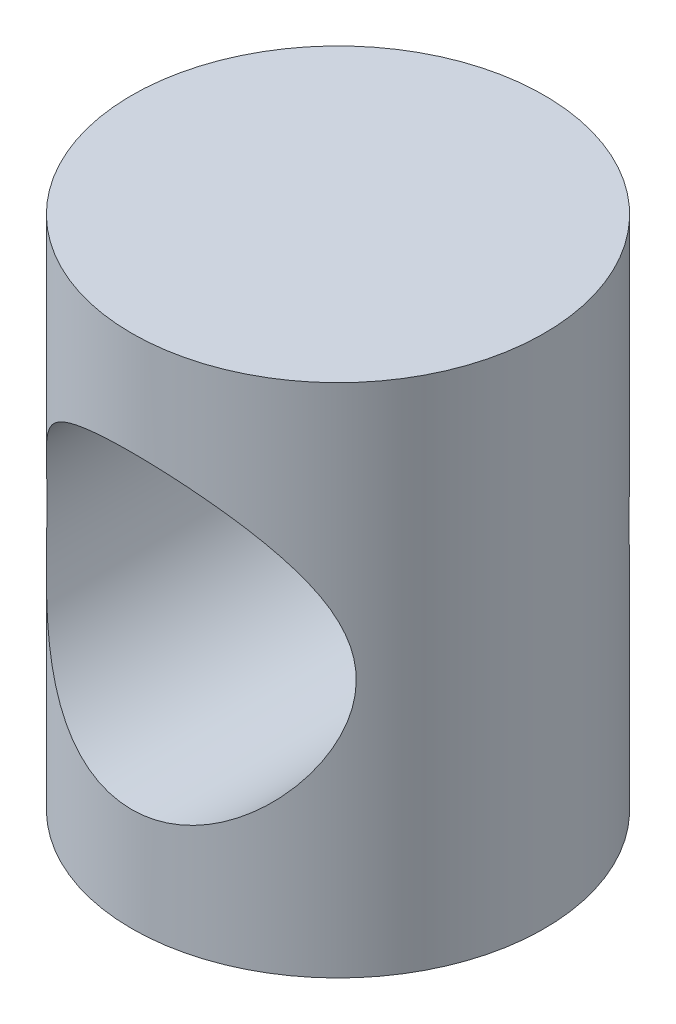
SolidWorks part; units mm, degrees
ref_plane "前视基准面" through (0, 0, 0) normal (0, 0, 1) x (1, 0, 0)
ref_plane "上视基准面" through (0, 0, 0) normal (0, 1, 0) x (1, 0, 0)
ref_plane "右视基准面" through (0, 0, 0) normal (1, 0, 0) x (0, 0, -1)
sketch "草图1" plane through (0, 0, 0) normal (0, 1, 0) x (1, 0, 0)
  line L1 (2, -2) -> (-2, -2)
  line L2 (2, -2) -> (2, 2)
  line L3 (2, 2) -> (-2, 2)
  line L4 (-2, -2) -> (-2, 2)
  line L5 (2, -2) -> (-2, 2) construction
  line L6 (2, 2) -> (-2, -2) construction
  point P0 (0, 0)
  dimension "4" = 4
extrude "凸台-拉伸2" add sketch "草图1" along normal blind 5
sketch "草图3" plane through (0, 0, 2) normal (0, 0, 1) x (1, 0, 0)
  line L0 (-2, 0) -> (2, 0) construction
  circle A0 centre (0, 2.5) radius 0.0235
  circle A1 centre (0, 2.5) radius 1.5
  dimension "3" = 3
  dimension "2.5" = 2.5
extrude "切除-拉伸2" cut sketch "草图3" against normal through all contours A1
cosmetic thread "装饰螺纹线1" parameters "D2"=4
sketch "草图6" plane through (0, 5, 0) normal (0, 1, 0) x (1, 0, 0)
  line L1 (2, -2) -> (-2, -2)
  line L2 (2, -2) -> (2, 2)
  line L3 (2, 2) -> (-2, 2)
  line L4 (-2, -2) -> (-2, 2)
  line L5 (2, -2) -> (-2, 2) construction
  line L6 (2, 2) -> (-2, -2) construction
  circle A0 centre (0, 0) radius 2
  line M2 (-2, 2) -> (-2, -2)
  line M3 (-2, -2) -> (2, -2)
  line M4 (2, -2) -> (2, 2)
  line M5 (2, 2) -> (-2, 2)
extrude "切除-拉伸14" cut sketch "草图6" against normal through all contours A0 L3 M2 | A0 L2 M5 | A0 L1 M4 | A0 L4 M3
